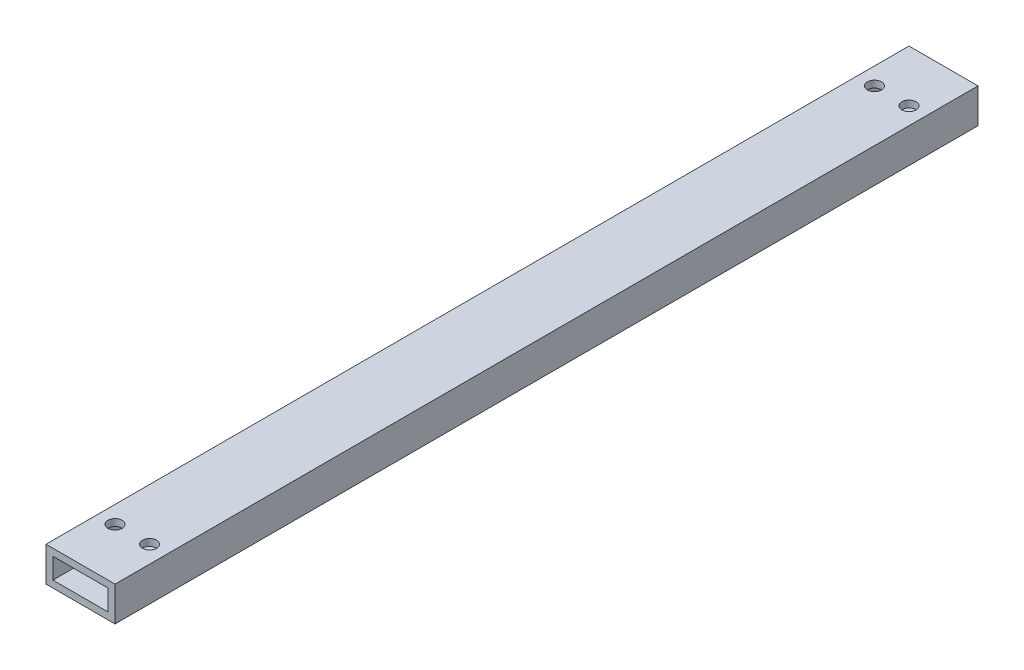
SolidWorks part; units mm, degrees
material "6063-T1"
ref_plane "前视基准面" through (0, 0, 0) normal (0, 0, 1) x (1, 0, 0)
ref_plane "上视基准面" through (0, 0, 0) normal (0, 1, 0) x (1, 0, 0)
ref_plane "右视基准面" through (0, 0, 0) normal (1, 0, 0) x (0, 0, -1)
other "Configuration Table"
sketch "草图1" plane through (0, 0, 0) normal (0, 0, 1) x (1, 0, 0)
  line L1 (-9.9632, 5.0382) -> (10.0368, 5.0382)
  line L2 (-9.9632, 5.0382) -> (-9.9632, -4.9618)
  line L3 (-9.9632, -4.9618) -> (10.0368, -4.9618)
  line L4 (10.0368, 5.0382) -> (10.0368, -4.9618)
  line L7 (-7.9632, 3.0382) -> (8.0368, 3.0382)
  line L8 (-7.9632, 3.0382) -> (-7.9632, -2.9618)
  line L9 (-7.9632, -2.9618) -> (8.0368, -2.9618)
  line L10 (8.0368, 3.0382) -> (8.0368, -2.9618)
  line L11 (-7.9632, 3.0382) -> (8.0368, -2.9618) construction
  line L12 (-7.9632, -2.9618) -> (8.0368, 3.0382) construction
  point P0 (0, 0)
  point P6 (0.0368, 0.0382)
  dimension "D1" = 20
  dimension "D2" = 10
  dimension "D3" = 2
  dimension "D4" = 2
  dimension "D5" = 2
  dimension "D6" = 2
extrude "凸台-拉伸1" add sketch "草图1" along normal mid plane 250
sketch "草图2" plane through (0, 5.0382, 0) normal (0, 1, 0) x (1, 0, 0)
  line L0 (0, 107) -> (0, 82) construction
  line L1 (5, 107) -> (5, 82)
  line L2 (-5, 107) -> (-5, 82)
  line L3 (10.0368, 125) -> (-9.9632, 125) construction
  arc A0 (5, 107) -> (-5, 107) centre (0, 107) ccw
  arc A1 (-5, 82) -> (5, 82) centre (0, 82) ccw
  point P3 (0, 94.5)
  dimension "D1" = 5
  dimension "D2" = 25
  dimension "D3" = 18
ref_plane "基准面1" through (0, 0, 0) normal (0, 0, 1) x (1, 0, 0)
sketch "草图3" plane through (0, 5.0382, 0) normal (0, 1, 0) x (1, 0, 0)
  line L0 (0.0368, 125) -> (0.0368, 121.9745) construction
  line L1 (10.0368, 125) -> (-9.9632, 125) construction
  circle A0 centre (-4.9632, 110) radius 2.05
  circle A2 centre (5.0368, 110) radius 2.05
  dimension "D1" = 4.1
  dimension "D2" = 10
  dimension "D3" = 15
extrude "切除-拉伸1" cut sketch "草图3" against normal through all
mirror "镜向1" about plane through (0, 0, 0) normal (0, 0, 1) of "切除-拉伸1"
